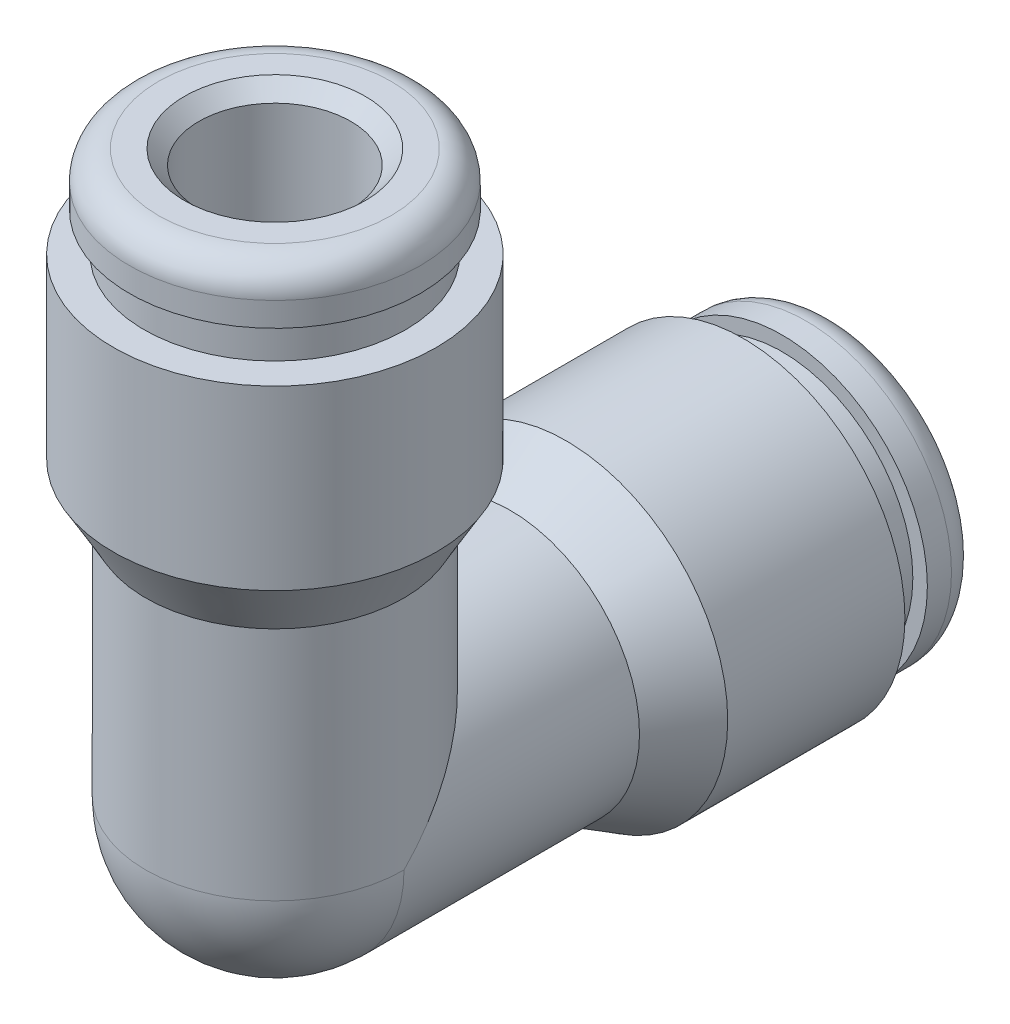
SolidWorks part; units mm, degrees
ref_plane "Front Plane" through (0, 0, 0) normal (0, 0, 1) x (1, 0, 0)
ref_plane "Top Plane" through (0, 0, 0) normal (0, 1, 0) x (1, 0, 0)
ref_plane "Right Plane" through (0, 0, 0) normal (1, 0, 0) x (0, 0, -1)
sketch "Sketch1" plane through (0, 0, 0) normal (1, 0, 0) x (0, 0, -1)
  line L0 (13.353, 3.825) -> (13.988, 3.825)
  line L1 (7.6722, 4.25) -> (12.337, 4.25)
  line L2 (0, 3.4) -> (0, 1.238)
  line L3 (5.25, 2) -> (14.369, 2)
  line L4 (14.75, 3.063) -> (14.75, 2.381)
  line L5 (0, 0) -> (0, 14.75) construction
  line L6 (12.337, 4.25) -> (12.337, 3.4425)
  line L7 (12.337, 3.4425) -> (13.353, 3.4425)
  line L8 (13.353, 3.825) -> (13.353, 3.4425)
  line L9 (-4.25, 14.75) -> (4.25, 14.75) construction
  line L10 (0, 0) -> (14.75, 0) construction
  line L11 (5.25, 2) -> (5.25, 1.238)
  line L12 (14.369, 2) -> (14.75, 2.381)
  line L13 (0, 0) -> (0, 1.238) construction
  line L14 (0, 3.4) -> (6.2, 3.4)
  line L15 (6.2, 3.4) -> (7.6722, 4.25)
  line L16 (5.25, 1.238) -> (0, 1.238)
  arc A0 (13.988, 3.825) -> (14.75, 3.063) centre (13.988, 3.063) cw
  point P1 (14.75, 2)
  point P20 (14.75, 3.825)
  dimension "D4" = 0.762
  dimension "tube od" = 4
  dimension "D1" = 1.397
  dimension "D2" = 1.016
  dimension "D3" = 6.885
  dimension "D6" = 7.65
  dimension "D9" = 30
  dimension "D10" = 6.8
  dimension "D5" = 8.55
  dimension "D8" = 8.5
  dimension "D11" = 0.762
revolve "Revolve1" add sketch "Sketch1" angle 360 about L10
ref_axis "Axis1" through (-15.8019, 0, 0) along (1, 0, 0)
pattern_circular "CirPattern1" count 2 over 90 about axis through (-15.8019, 0, 0) along (1, 0, 0) of bodies 118 123
sketch "Sketch2" plane through (0, 0, 0) normal (0, 0, 1) x (1, 0, 0)
  line L0 (-3.4, 0) -> (-1.238, 0)
  line L1 (-3.4, 0) -> (3.4, 0) construction
  line L2 (1.238, 0) -> (3.4, 0)
  arc A0 (-3.4, 0) -> (3.4, 0) centre (0, 0) ccw
  arc A2 (-1.238, 0) -> (1.238, 0) centre (0, 0) ccw
  circle A4 centre (0, 0) radius 1.238 construction
  circle A5 centre (0, 0) radius 3.4 construction
revolve "Revolve2" add sketch "Sketch2" angle 90 about L1
combine bodies "Combine1" operation type add bodies to combine 122 124
sketch "Sketch3" plane through (0, 0, 0) normal (1, 0, 0) x (0, 0, -1)
  line L0 (14.75, 2.381) -> (14.369, 2)
  line L1 (14.369, 2) -> (5.25, 2)
  line L2 (5.25, 2) -> (5.25, 1.238)
  line L3 (5.25, 1.238) -> (0, 1.238)
  line L4 (0, 1.238) -> (0, 0)
  line L5 (0, 0) -> (14.75, 0)
  line L6 (14.75, 0) -> (14.75, 2.381)
revolve "Cut-Revolve1" cut sketch "Sketch3" angle 360 about L5
pattern_circular "CirPattern2" count 2 over 90 about axis through (-15.8019, 0, 0) along (1, 0, 0) of "Cut-Revolve1"
equation "\"D6@Sketch1\" = \"G@Sketch1\"*.9"
equation "\"D3@Sketch1\" = \"D6@Sketch1\"*.9"
equation "\"D10@Sketch1\" = \"G@Sketch1\"*.8"
equation "\"D5@Sketch1\" = \"L@Sketch1\"*.45"
equation "\"D8@Sketch1\" = \"G@Sketch1\""
